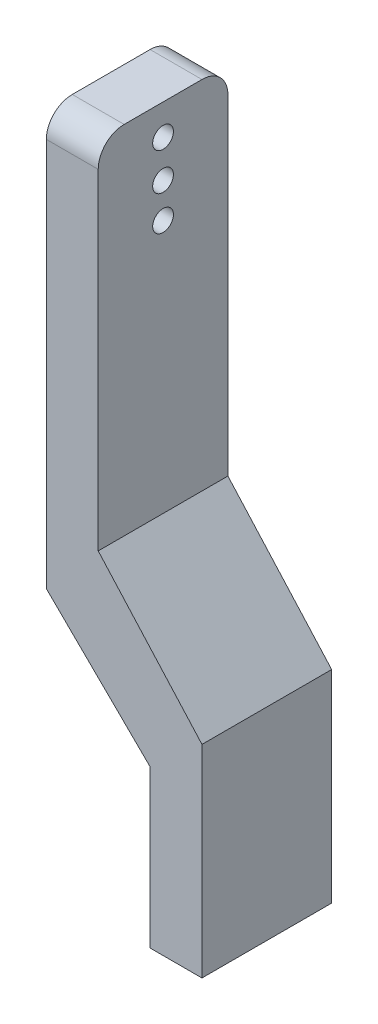
SolidWorks part; units mm, degrees
ref_plane "Ön Düzlem" through (0, 0, 0) normal (0, 0, 1) x (1, 0, 0)
ref_plane "Üst Düzlem" through (0, 0, 0) normal (0, 1, 0) x (1, 0, 0)
ref_plane "Sağ Düzlem" through (0, 0, 0) normal (1, 0, 0) x (0, 0, -1)
sketch "Çizim1" plane through (0, 0, 0) normal (0, 0, 1) x (1, 0, 0)
  line L0 (0, 0) -> (0, 80)
  line L1 (0, 80) -> (10, 80)
  line L2 (10, 80) -> (10, 11.2973)
  line L5 (30, -50) -> (20, -50)
  line L6 (20, -50) -> (20, -19.7362)
  line L9 (10, -10) -> (20, -19.7362)
  line L12 (20, -19.7362) -> (0, 0)
  line L13 (10, 11.2973) -> (30, -11.0028)
  line L14 (30, -11.0028) -> (30, -50)
extrude "Yükseklik-Ekstrüzyon1" add sketch "Çizim1" along normal blind 25 contours L14 L13 L2 L1 L0 L12 L6 L5
sketch "Çizim2" plane through (0, 0, 0) normal (-1, 0, 0) x (0, 0, 1)
  line L0 (25, 80) -> (25, 0)
  line L1 (25, 0) -> (0, 0)
  line L2 (0, 0) -> (0, 80)
  line L3 (0, 80) -> (25, 80)
  line L4 (0, 80) -> (0, 0)
  line L5 (25, 0) -> (0, 0)
  line L6 (12.5, 80) -> (12.5, 0)
  circle A0 centre (12.5, 74.0889) radius 2
  circle A1 centre (12.5, 66.9039) radius 2
  circle A2 centre (12.5, 60.2077) radius 2
extrude "Kes-Ekstrüzyon1" cut sketch "Çizim2" against normal blind 25 contours L6 A0 | L6 A0 | L6 A1 | L6 A1 | L6 A2 | L6 A2
fillet "Radyus1" radius 5 1 edges at (5, 80, 25)
fillet "Radyus2" radius 5 1 edges at (5, 80, 0)
